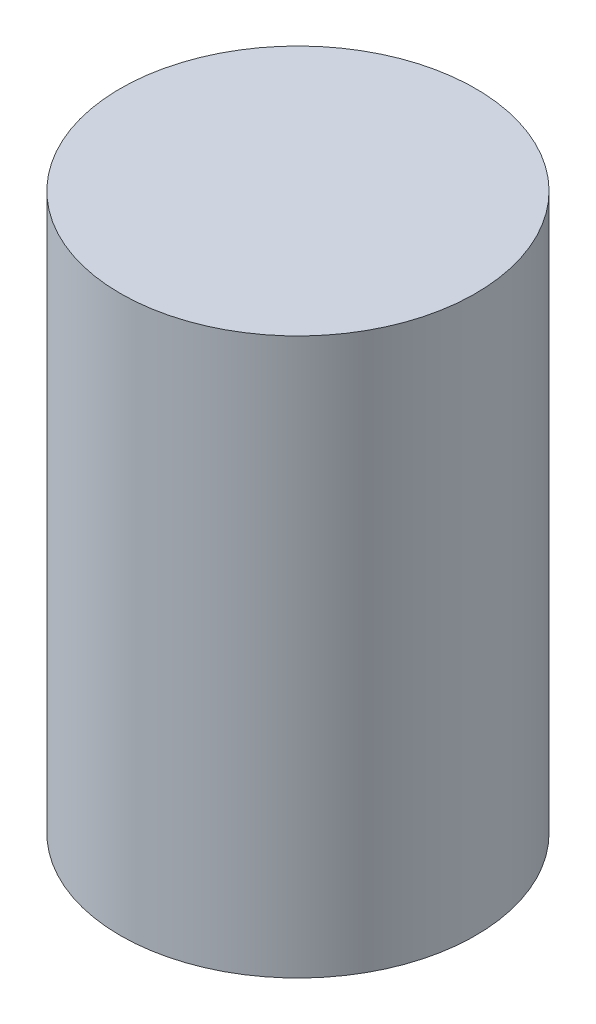
SolidWorks part; units mm, degrees
ref_plane "Front Plane" through (0, 0, 0) normal (0, 0, 1) x (1, 0, 0)
ref_plane "Top Plane" through (0, 0, 0) normal (0, 1, 0) x (1, 0, 0)
ref_plane "Right Plane" through (0, 0, 0) normal (1, 0, 0) x (0, 0, -1)
sketch "Sketch1" plane through (0, 0, 0) normal (0, 1, 0) x (1, 0, 0)
  circle A0 centre (0, 0) radius 9.9
  dimension "D1" = 19.8
extrude "Boss-Extrude1" add sketch "Sketch1" along normal blind 31
